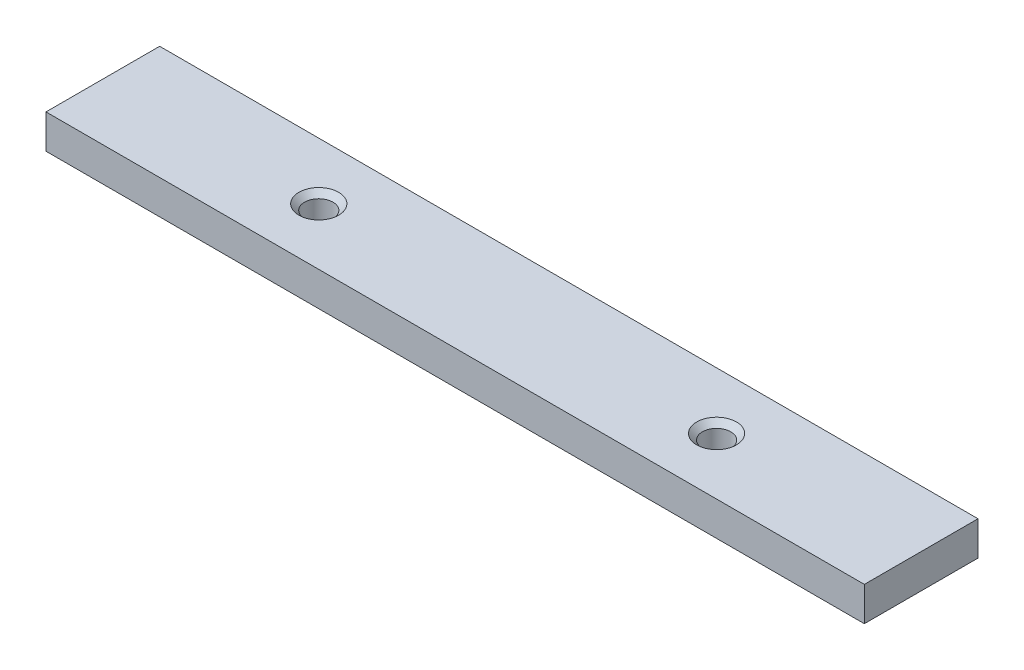
SolidWorks part; units mm, degrees
material "A286 Iron Base Superalloy"
ref_plane "Front Plane" through (0, 0, 0) normal (0, 0, 1) x (1, 0, 0)
ref_plane "Top Plane" through (0, 0, 0) normal (0, 1, 0) x (1, 0, 0)
ref_plane "Right Plane" through (0, 0, 0) normal (1, 0, 0) x (0, 0, -1)
sketch "Sketch2" plane through (0, 0, 0) normal (0, 1, 0) x (1, 0, 0)
  line L1 (72, 10) -> (-72, 10)
  line L2 (72, 10) -> (72, -10)
  line L3 (72, -10) -> (-72, -10)
  line L4 (-72, 10) -> (-72, -10)
  line L5 (72, 10) -> (-72, -10) construction
  line L6 (72, -10) -> (-72, 10) construction
  point P0 (0, 0)
  dimension "D1" = 20
  dimension "D2" = 144
extrude "Boss-Extrude1" add sketch "Sketch2" along normal mid plane 6
sketch "Sketch3" plane through (0, 3, 0) normal (0, 1, 0) x (1, 0, 0)
  line L0 (-72, 10) -> (-72, -10) construction
  line L1 (-72, -10) -> (72, -10) construction
  circle A0 centre (-34, 0) radius 3.5
  circle A1 centre (36, 0) radius 3.5
  dimension "D1" = 7
  dimension "D2" = 7
  dimension "D3" = 70
  dimension "D4" = 38
  dimension "D5" = 10
hole_wizard "CSK for #0 Flat Head Machine Screw (100)1" positions "3DSketch1" profile "Sketch4" countersink size "#0" standard "ANSI Inch" end condition through all
sketch3d "3DSketch1"
  point P0 (-34, 3, 0)
  point P3 (36, 3, 0)
sketch "Sketch4" plane through (-34, 3, 0) normal (1, 0, 0) x (0, 0, 1)
  line L0 (0, 0) -> (0, 6)
  line L1 (0, 6) -> (2.5, 6)
  line L2 (2.5, 6) -> (2.5, 1)
  line L3 (2.5, 1) -> (3.5, 0)
  line L5 (3.5, 0) -> (0, 0)
  line L6 (-2.5, 1) -> (-3.5, 0) construction
  line L11 (0, -6.35) -> (0, 107.95) construction
  dimension "Thru Hole Dia." = 5
  dimension "Thru Hole Depth" = 6
  dimension "Near C'Sink Dia." = 7
  dimension "Near C'Sink Angle" = 90
